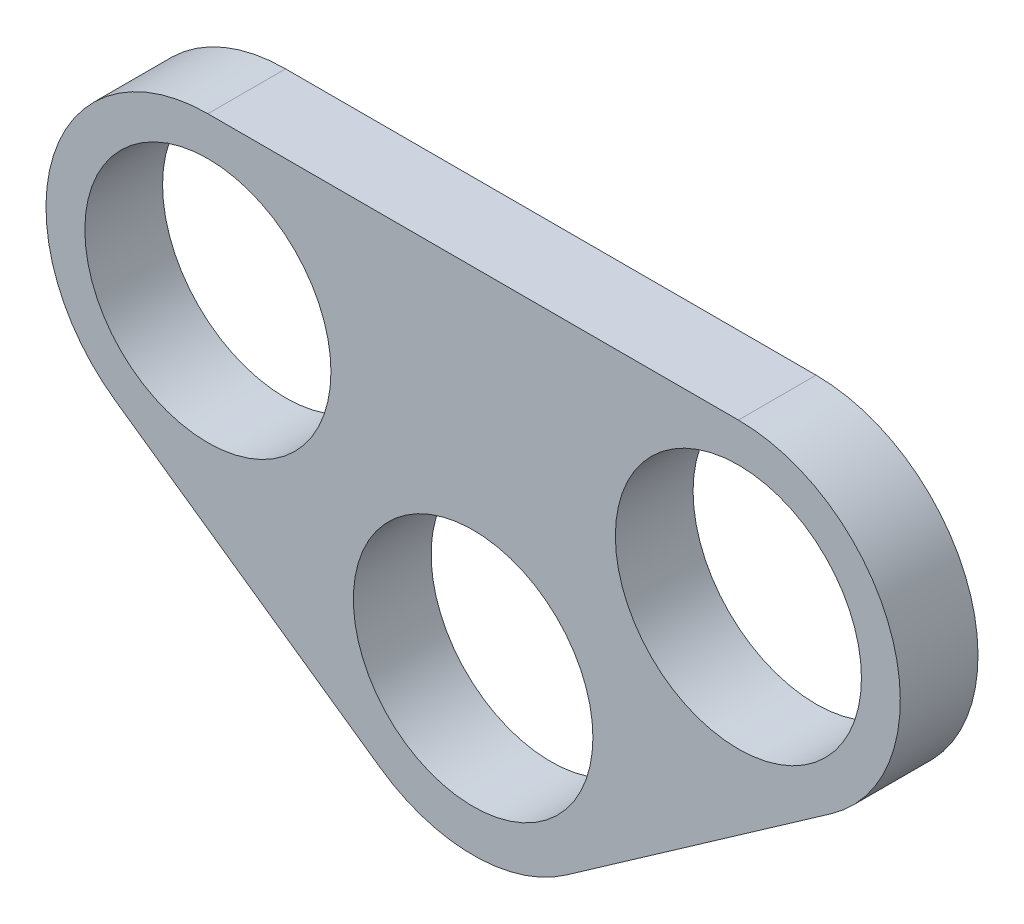
SolidWorks part; units mm, degrees
ref_plane "Alzado" through (0, 0, 0) normal (0, 0, 1) x (1, 0, 0)
ref_plane "Planta" through (0, 0, 0) normal (0, 1, 0) x (1, 0, 0)
ref_plane "Vista lateral" through (0, 0, 0) normal (1, 0, 0) x (0, 0, -1)
sketch "Croquis1" plane through (0, 0, 0) normal (0, 0, 1) x (1, 0, 0)
  line L0 (0, 0) -> (20.4788, 14.3394) construction
  line L1 (0, 0) -> (-20.4788, 14.3394) construction
  line L2 (-20.4788, 26.8394) -> (20.4788, 26.8394)
  line L3 (10.2394, 7.1697) -> (20.4788, 14.3394) construction
  line L4 (20.4788, 14.3394) -> (33.1523, -3.7602) construction
  line L5 (10.2394, 7.1697) -> (0, 0) construction
  line L6 (0, 0) -> (10.8766, -15.5333) construction
  line L7 (20.4788, 14.3394) -> (0, 0) construction
  line L8 (-27.6485, 4.1) -> (-7.1697, -10.2394)
  line L9 (0, 0) -> (-20.4788, 14.3394) construction
  line L10 (-20.4788, 14.3394) -> (-33.1523, -3.7602) construction
  line L12 (7.1697, -10.2394) -> (27.6485, 4.1)
  line L13 (-20.4788, 14.3394) -> (0, 0) construction
  line L14 (0, 0) -> (-13.5353, -19.3304) construction
  circle A0 centre (0, 0) radius 9.2478
  circle A1 centre (0, 0) radius 12.5
  circle A2 centre (-20.4788, 14.3394) radius 12.5
  circle A3 centre (20.4788, 14.3394) radius 12.5
  circle A4 centre (-20.4788, 14.3394) radius 9.5
  circle A5 centre (20.4788, 14.3394) radius 9.5
  dimension "D1" = 25
  dimension "D2" = 18.4955
  dimension "D5" = 19
  dimension "D6" = 19
  dimension "D8" = 14.3394
  dimension "D3" = 25
  dimension "D4" = 25
  dimension "D7" = 40.9576
extrude "Saliente-Extruir1" add sketch "Croquis1" along normal blind 6 contours A3 L2 A2 A1 | A2 L8 A1 | A3 A1 L12 | A1 A0 | A2 A4 | A3 A5
